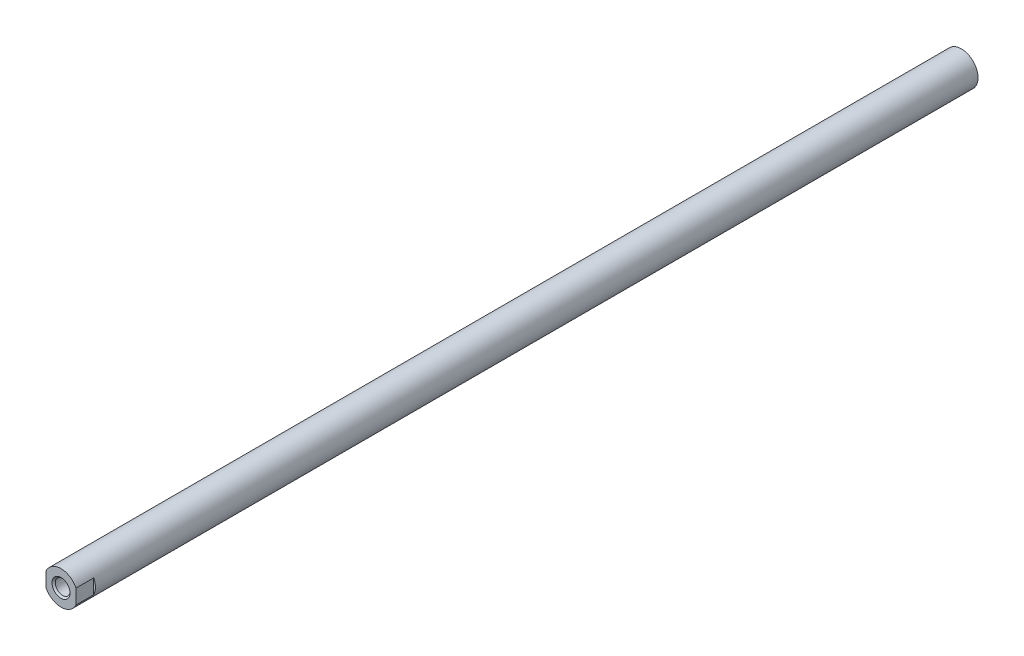
SolidWorks part; units mm, degrees
ref_plane "Front Plane" through (0, 0, 0) normal (0, 0, 1) x (1, 0, 0)
ref_plane "Top Plane" through (0, 0, 0) normal (0, 1, 0) x (1, 0, 0)
ref_plane "Right Plane" through (0, 0, 0) normal (1, 0, 0) x (0, 0, -1)
ref_plane "Plane1" through (0, 0, 0) normal (0, -1, 0) x (1, 0, 0)
sketch "Sketch1" plane through (0, 0, 0) normal (0, -1, 0) x (1, 0, 0)
  line L0 (5.5644, 5.5644) -> (0, 5.5644)
  line L1 (0, 5.5644) -> (0, -294.4356)
  line L2 (0, -294.4356) -> (5.5644, -294.4356)
  line L3 (5.5644, -294.4356) -> (5.5644, 5.5644)
  line L4 (0, 5.5644) -> (0, -294.4356) construction
  dimension "D1" = 300
revolve "Revolve1" add sketch "Sketch1" angle 360 about L4
sketch "Sketch2" plane through (0, 0, 5.5644) normal (0, 0, 1) x (1, 0, 0)
  line L0 (-5, -3.3166) -> (-5, 3.3166)
  arc A0 (-5, 3.3166) -> (-5, -3.3166) centre (0, 0) ccw
extrude "Cut-Extrude1" cut sketch "Sketch2" against normal blind 5.9
sketch "Sketch3" plane through (0, 0, 5.5644) normal (0, 0, 1) x (1, 0, 0)
  line L0 (5, 3.3166) -> (5, -3.3166)
  arc A0 (5, -3.3166) -> (5, 3.3166) centre (0, 0) ccw
extrude "Cut-Extrude2" cut sketch "Sketch3" against normal blind 5.9
hole_wizard "Hole1" positions "Sketch5" profile "Sketch4" legacy
sketch "Sketch5" plane through (0, 0, 5.5644) normal (0, 0, 1) x (1, 0, 0)
  point P0 (0, 0)
sketch "Sketch4" plane through (0, 0, 5.5644) normal (1, 0, 0) x (0, -1, 0)
  line L0 (0, 0) -> (0, 11.9203)
  line L1 (0, 11.9203) -> (2.46, 10.5)
  line L2 (2.46, 10.5) -> (2.46, 0)
  line L4 (2.46, 0) -> (0, 0)
  line L6 (0, 11.9203) -> (-2.46, 10.5) construction
  line L7 (0, -4.2442) -> (0, 117.3081) construction
  dimension "Diameter" = 4.92
  dimension "Depth" = 10.5
  dimension "Drill Angle" = 120
chamfer "Chamfer2" distance 0.54 angle 45 1 edges at (2.46, 0, 5.5644)
